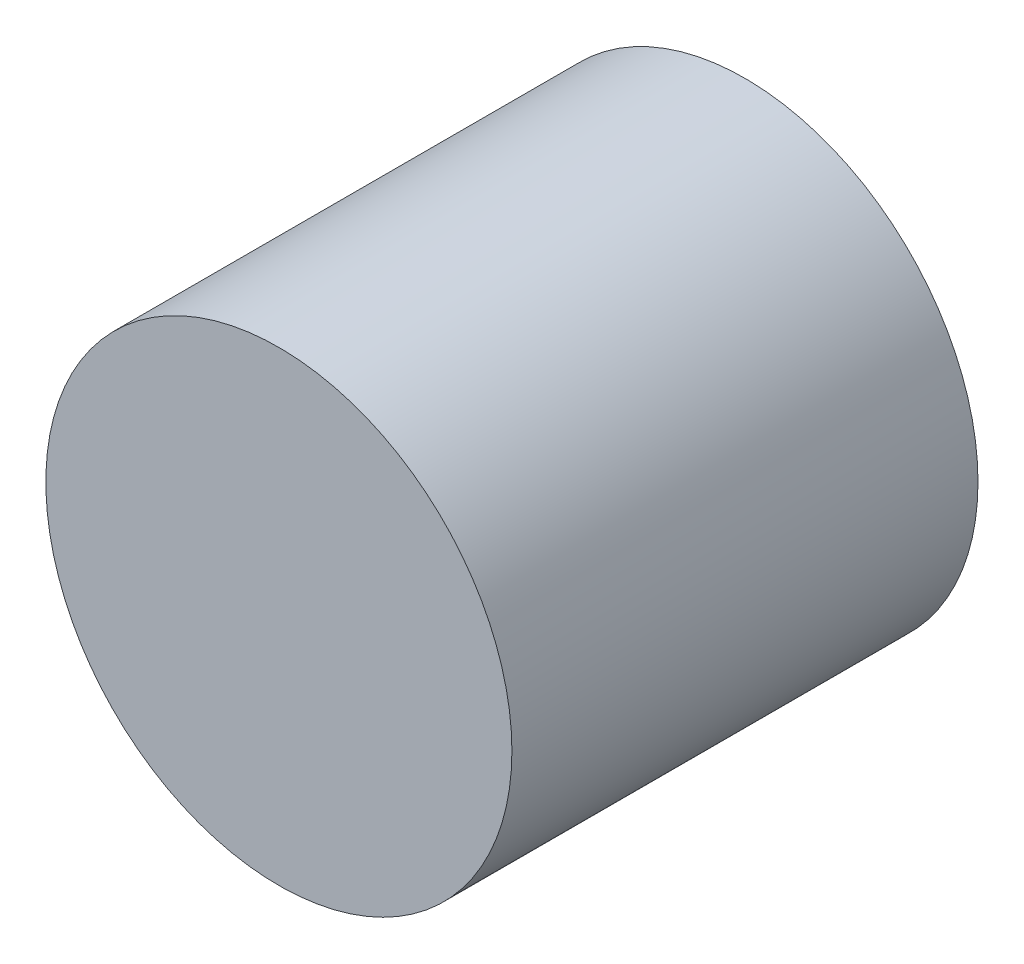
SolidWorks part; units mm, degrees
material "Nylon"
ref_plane "Front Plane" through (0, 0, 0) normal (0, 0, 1) x (1, 0, 0)
ref_plane "Top Plane" through (0, 0, 0) normal (0, 1, 0) x (1, 0, 0)
ref_plane "Right Plane" through (0, 0, 0) normal (1, 0, 0) x (0, 0, -1)
sketch "Sketch1" plane through (0, 0, 0) normal (1, 0, 0) x (0, 0, -1)
  line L0 (0, 0) -> (7.8365, 0) construction
  line L1 (0, 0) -> (0, 2)
  line L2 (0, 2) -> (4, 2)
  line L3 (4, 2) -> (4, 0)
  line L4 (0, 0) -> (4, 0)
  dimension "D1" = 4
  dimension "D2" = 4
revolve "Revolve1" add sketch "Sketch1" angle 360 about L0
cosmetic thread "Cosmetic Thread1" parameters "D2"=3.3
sketch "Sketch2" [suppressed] plane through (0, 0, -6) normal (0, 0, -1) x (-1, 0, 0)
  line L1 (2.8868, 0) -> (1.4434, 2.5)
  line L2 (1.4434, 2.5) -> (-1.4434, 2.5)
  line L3 (-1.4434, 2.5) -> (-2.8868, 0)
  line L4 (-2.8868, 0) -> (-1.4434, -2.5)
  line L5 (-1.4434, -2.5) -> (1.4434, -2.5)
  line L6 (1.4434, -2.5) -> (2.8868, 0)
  circle A0 centre (0, 0) radius 2.5 construction
  dimension "D1" = 5
extrude "Boss-Extrude1" [suppressed] add sketch "Sketch2" along normal blind 3
